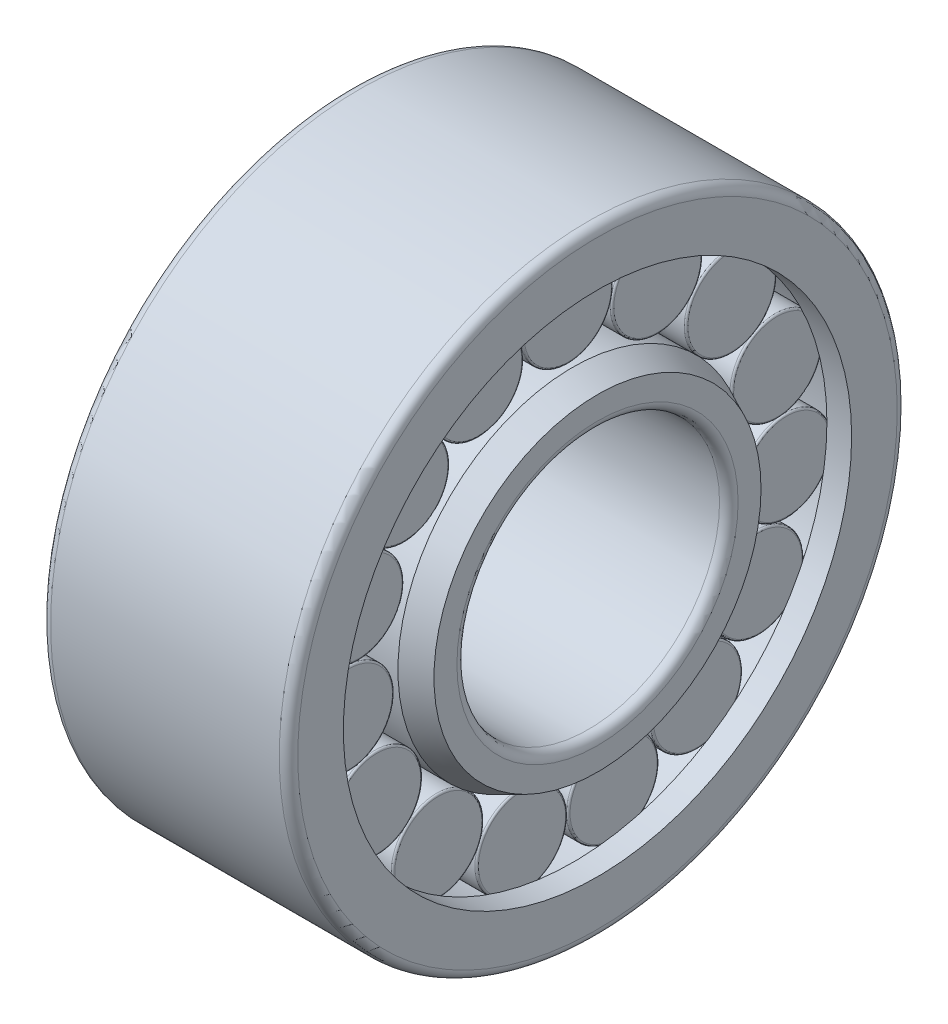
SolidWorks part; units mm, degrees
ref_plane "Plane1" through (0, 0, 0) normal (0, 0, 1) x (1, 0, 0)
ref_plane "Plane2" through (0, 0, 0) normal (0, 1, 0) x (1, 0, 0)
ref_plane "Plane3" through (0, 0, 0) normal (1, 0, 0) x (0, 0, -1)
sketch "Clipboard" plane through (0, 0, 0) normal (0, 0, 1) x (1, 0, 0)
  line L0 (-10, 0) -> (10, 0) construction
  line L1 (0, 0) -> (21.8637, -5.8584)
  line L2 (0, 0) -> (14.2478, -0.2487)
  line L3 (0, 0) -> (34.3598, 0.5998)
  line L4 (0, 0) -> (-22.3573, -0.3902)
  dimension "CLdia" = 14.25
  dimension "Count" = 359
  dimension "Show_count" = 359
  dimension "Max_count" = 15
  dimension "Min_count" = 1
  dimension "Race_OD" = 34.365
  dimension "Race_ID" = 22.635
sketch "OutRacSke" plane through (0, 0, 0) normal (0, 0, 1) x (1, 0, 0)
  line L0 (-6.4, 16.4494) -> (-8, 16.4494)
  line L1 (-8, 16.4494) -> (-8, 19.4)
  line L2 (-7.4, 20) -> (7.4, 20)
  line L3 (8, 19.4) -> (8, 16.4494)
  line L4 (8, 16.4494) -> (6.4, 16.4494)
  line L5 (6.4, 16.4494) -> (6.4, 17.1825)
  line L6 (6.4, 17.1825) -> (-6.4, 17.1825)
  line L7 (-6.4, 17.1825) -> (-6.4, 16.4494)
  line L8 (-90, 0) -> (90, 0) construction
  arc A0 (-8, 19.4) -> (-7.4, 20) centre (-7.4, 19.4) cw
  arc A1 (7.4, 20) -> (8, 19.4) centre (7.4, 19.4) cw
  dimension "Race_OD" = 34.365
  dimension "radius" = 0.6
  dimension "OD" = 40
  dimension "Cyl_Len" = 12.8
  dimension "halfCylLen" = 6.4
  dimension "Width" = 16
  dimension "halfWidth" = 8
  dimension "groove_dp" = 0.7331
revolve "OuterRace" add sketch "OutRacSke" angle 360 about L8
sketch "RolDetSke" plane through (0, 0, 0) normal (0, 0, 1) x (1, 0, 0)
  line L0 (-6.08, 17.07) -> (-6.08, 14.25)
  line L1 (-6.08, 14.25) -> (6.08, 14.25)
  line L2 (6.08, 14.25) -> (6.08, 17.07)
  line L3 (5.9625, 17.1875) -> (-5.9625, 17.1875)
  line L4 (-33.6, 14.25) -> (33.6, 14.25) construction
  arc A0 (6.08, 17.07) -> (5.9625, 17.1875) centre (5.9625, 17.07) ccw
  arc A1 (-5.9625, 17.1875) -> (-6.08, 17.07) centre (-5.9625, 17.07) ccw
  dimension "radius" = 0.1175
  dimension "RolCLRad" = 14.25
  dimension "Length" = 12.16
  dimension "halfLength" = 6.08
  dimension "Roller_diameter" = 5.875
revolve "RollerDetailed" add sketch "RolDetSke" angle 360 about L4
ref_axis "Axis1" through (-50, 0, 0) along (1, 0, 0)
sketch "RolSimSke" plane through (0, 101.6, 0) normal (0, 0, 1) x (1, 0, 0)
  line L0 (-6.08, -84.53) -> (-6.08, -90.17)
  line L1 (25.4, -101.6) -> (-25.4, -101.6) construction
  line L2 (6.08, -90.17) -> (6.08, -84.53)
  line L3 (5.9625, -84.4125) -> (-5.9625, -84.4125)
  line L5 (5.9625, -90.2875) -> (-5.9625, -90.2875)
  arc A0 (6.08, -84.53) -> (5.9625, -84.4125) centre (5.9625, -84.53) ccw
  arc A1 (-5.9625, -84.4125) -> (-6.08, -84.53) centre (-5.9625, -84.53) ccw
  arc A2 (6.08, -90.17) -> (5.9625, -90.2875) centre (5.9625, -90.17) cw
  arc A3 (-5.9625, -90.2875) -> (-6.08, -90.17) centre (-5.9625, -90.17) cw
  dimension "radius" = 0.1175
  dimension "halfLength" = 6.08
  dimension "Roller_diameter" = 5.875
  dimension "D1" = 11.3125
  dimension "Rol_Length" = 12.16
revolve "RollersSimplified" [suppressed] add sketch "RolSimSke" angle 360 about L1
sketch "InsRacSke" plane through (0, 0, 0) normal (0, 0, 1) x (1, 0, 0)
  line L0 (-6.4, 11.3175) -> (-8, 10.5844)
  line L1 (-8, 10.5844) -> (-8, 9.1)
  line L2 (-7.4, 8.5) -> (7.4, 8.5)
  line L3 (8, 9.1) -> (8, 10.5844)
  line L4 (8, 10.5844) -> (6.4, 11.3175)
  line L5 (6.4, 11.3175) -> (-6.4, 11.3175)
  line L6 (-90, 0) -> (90, 0) construction
  line L7 (0, 0) -> (0, 177.8) construction
  arc A0 (-8, 9.1) -> (-7.4, 8.5) centre (-7.4, 9.1) ccw
  arc A1 (7.4, 8.5) -> (8, 9.1) centre (7.4, 9.1) ccw
  dimension "Race_ID" = 22.635
  dimension "radius" = 0.6
  dimension "Cyl_Len" = 12.8
  dimension "Width" = 16
  dimension "halfWidth" = 8
  dimension "groove_dp" = 0.7331
  dimension "Bore" = 17
revolve "InnerRace" add sketch "InsRacSke" angle 360 about L6
pattern_circular "RollersDetailed" count 15 every 24 about axis through (-50, 0, 0) along (1, 0, 0) of "RollerDetailed"
sketch "CagSpiSke" plane through (0, 0, 0) normal (0, 0, 1) x (1, 0, 0)
  line L0 (7.2, 13.5156) -> (7.2, 14.9844)
  line L1 (7.2, 14.9844) -> (-7.2, 14.9844)
  line L2 (-7.2, 14.9844) -> (-7.2, 13.5156)
  line L3 (-7.2, 13.5156) -> (7.2, 13.5156)
  line L4 (-90, 0) -> (90, 0) construction
  dimension "Cag_IR" = 27.0312
  dimension "thickness" = 1.4688
  dimension "width" = 14.4
  dimension "halfwidth" = 7.2
revolve "CageSpine" [suppressed] add sketch "CagSpiSke" angle 0.001 about L4
equation "\"CLdia@Clipboard\" =  ( \"Race_OD@Clipboard\" + \"Race_ID@Clipboard\" )  / 4"
equation "\"Race_OD@OutRacSke\" = \"Race_OD@Clipboard\""
equation "\"halfCylLen@OutRacSke\" = \"Cyl_Len@OutRacSke\" / 2"
equation "\"RolCLRad@RolDetSke\" = \"CLdia@Clipboard\""
equation "\"Roller_diameter@RolDetSke\" =  ( \"Race_OD@Clipboard\" - \"Race_ID@Clipboard\" )  / 2 + .01"
equation "\"Roller_diameter@RolSimSke\" =  ( \"Race_OD@Clipboard\" - \"Race_ID@Clipboard\" )  / 2 + .01"
equation "\"radius@RolDetSke\" = \"Roller_diameter@RolDetSke\" / 50"
equation "\"Length@RolDetSke\" = \"Cyl_Len@OutRacSke\" * .95"
equation "\"halfLength@RolDetSke\" = \"Length@RolDetSke\" / 2"
equation "\"thickness@CagSpiSke\"  = \"Roller_diameter@RolDetSke\" * .25"
equation "\"Cag_IR@CagSpiSke\" =  \"RolCLRad@RolDetSke\" * 2 - \"thickness@CagSpiSke\""
equation "\"Rol_Length@RolSimSke\" = \"Cyl_Len@InsRacSke\" * .95"
equation "\"halfLength@RolSimSke\" = \"Rol_Length@RolSimSke\" / 2"
equation "\"radius@RolSimSke\" = \"radius@RolDetSke\""
equation "\"D1@RolSimSke\" = \"CLdia@Clipboard\" -  ( \"Roller_diameter@RolSimSke\" / 2 ) "
equation "\"Max_count@Clipboard\" = int( 3.14159265 / atn(( \"Roller_diameter@RolDetSke\" / 2) / sqr( \"RolCLRad@RolDetSke\"  *  \"RolCLRad@RolDetSke\" - ( \"Roller_diameter@RolDetSke\" / 2) *  ( \"Roller_diameter@RolDetSke\" / 2))))"
equation "\"Max_count@Clipboard\" = ((sgn( \"Max_count@Clipboard\" - \"Count@Clipboard\" )-1)*( \"Max_count@Clipboard\" - \"Count@Clipboard\" ))/-2+ \"Count@Clipboard\""
equation "\"Count@RollersDetailed\" = int( \"Show_count@Clipboard\" ) "
equation "\"Count@RollersDetailed\" = ((sgn( \"Count@RollersDetailed\" - \"Max_count@Clipboard\" )-1)*( \"Count@RollersDetailed\" - \"Max_count@Clipboard\" ))/-2+ \"Max_count@Clipboard\""
equation "\"Count@RollersDetailed\" = ((sgn( \"Count@RollersDetailed\" - \"Min_count@Clipboard\" )+1)*( \"Count@RollersDetailed\" - \"Min_count@Clipboard\"))/2 +\"Min_count@Clipboard\""
equation "\"Angle@RollersDetailed\" = 360.0 / \"Max_count@Clipboard\""
equation "\"radius@InsRacSke\" = \"radius@OutRacSke\""
equation "\"groove_dp@InsRacSke\" = \"groove_dp@OutRacSke\""
equation "\"Width@InsRacSke\" = \"Width@OutRacSke\""
equation "\"halfWidth@OutRacSke\" = \"Width@OutRacSke\" / 2"
equation "\"halfWidth@InsRacSke\" = \"Width@InsRacSke\" / 2"
equation "\"Race_ID@InsRacSke\" = \"Race_ID@Clipboard\""
equation "\"Cyl_Len@InsRacSke\" = \"Cyl_Len@OutRacSke\""
equation "\"Angle@CageSpine\" =  \"Angle@RollersDetailed\" * ( \"Count@RollersDetailed\" -1 + int( \"Count@RollersDetailed\" / \"Max_count@Clipboard\" ) )  + 0.001 -  int( \"Count@RollersDetailed\" / \"Max_count@Clipboard\" ) * 0.001"
equation "\"Angle@CageSpine\" =  \"Angle@CageSpine\" * int( \"Min_count@Clipboard\" / 2) + int(1 / \"Min_count@Clipboard\")  * 0.001"
equation "\"width@CagSpiSke\" =   ( \"Width@InsRacSke\" + \"Cyl_Len@InsRacSke\" )  / 2"
equation "\"halfwidth@CagSpiSke\" = \"width@CagSpiSke\" / 2"
